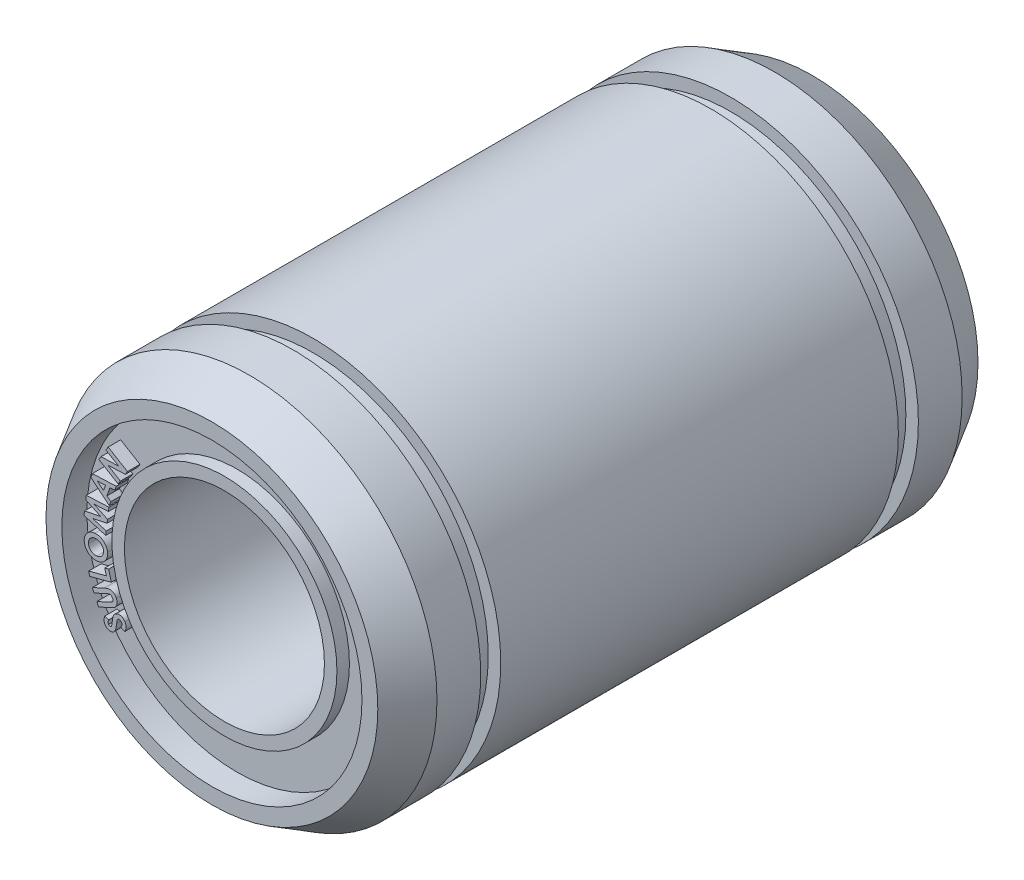
SolidWorks part; units mm, degrees
ref_plane "Front Plane" through (0, 0, 0) normal (0, 0, 1) x (1, 0, 0)
ref_plane "Top Plane" through (0, 0, 0) normal (0, 1, 0) x (1, 0, 0)
ref_plane "Right Plane" through (0, 0, 0) normal (1, 0, 0) x (0, 0, -1)
sketch "Sketch1" plane through (0, 0, 0) normal (0, 0, 1) x (1, 0, 0)
  circle A0 centre (0, 0) radius 7.5
  circle A1 centre (0, 0) radius 6
  dimension "D1" = 15
  dimension "D2" = 12
extrude "Boss-Extrude1" add sketch "Sketch1" along normal mid plane 24
chamfer "Chamfer2" distance 1.5 angle 30 1 edges at (7.5, 0, 12)
sketch "Sketch5" plane through (0, 0, 0) normal (0, 0, 1) x (1, 0, 0)
  circle A0 centre (0, 0) radius 6
  circle A1 centre (0, 0) radius 4
  dimension "D1" = 8
extrude "Boss-Extrude2" add sketch "Sketch5" along normal blind 11 and the other way blind 11 separate body
sketch "Sketch6" plane through (0, 0, 11) normal (0, 0, 1) x (1, 0, 0)
  circle A0 centre (0, 0) radius 4
  circle A1 centre (0, 0) radius 4.5
  dimension "D1" = 9
extrude "Boss-Extrude3" add sketch "Sketch6" along normal blind 0.5
mirror "Mirror1" about plane through (0, 0, 0) normal (0, 0, 1) of "Boss-Extrude3"
sketch "Sketch7" plane through (0, 0, 0) normal (1, 0, 0) x (0, 0, -1)
  line L0 (12, 7.5) -> (-10.5, 7.5) construction
  line L1 (-8.75, 7.5) -> (-7.95, 7.5)
  line L2 (-8.75, 7.5) -> (-8.75, 7)
  line L3 (-8.75, 7) -> (-7.95, 7)
  line L4 (-7.95, 7.5) -> (-7.95, 7)
  line L5 (0, 0) -> (5.2365, 0) construction
  line L6 (7.95, 7.5) -> (8.75, 7.5)
  line L7 (7.95, 7.5) -> (7.95, 7)
  line L8 (7.95, 7) -> (8.75, 7)
  line L9 (8.75, 7.5) -> (8.75, 7)
  dimension "D1" = 17.5
  dimension "D2" = 0.8
  dimension "D3" = 0.8
  dimension "D4" = 7.95
  dimension "D5" = 0.5
  dimension "D6" = 0.5
revolve "Cut-Revolve1" cut sketch "Sketch7" angle 360 about L5
sketch "Sketch8" plane through (0, 0, 11) normal (0, 0, 1) x (1, 0, 0)
  circle A0 centre (0, 0) radius 4.7503 construction
  text T0 "SULOMAN" font "Century Gothic" height 0.9
extrude "Boss-Extrude4" add sketch "Sketch8" along normal blind 0.5
ref_plane "Plane1" through (7.5, 0, 0) normal (1, 0, 0) x (0, 0, -1)
chamfer "Chamfer3" distance 1.5 angle 30 1 edges at (7.5, 0, -12)
sketch "Sketch10" plane through (0, 0, -11) normal (0, 0, -1) x (-1, 0, 0)
  circle A0 centre (0, 0) radius 7.5
